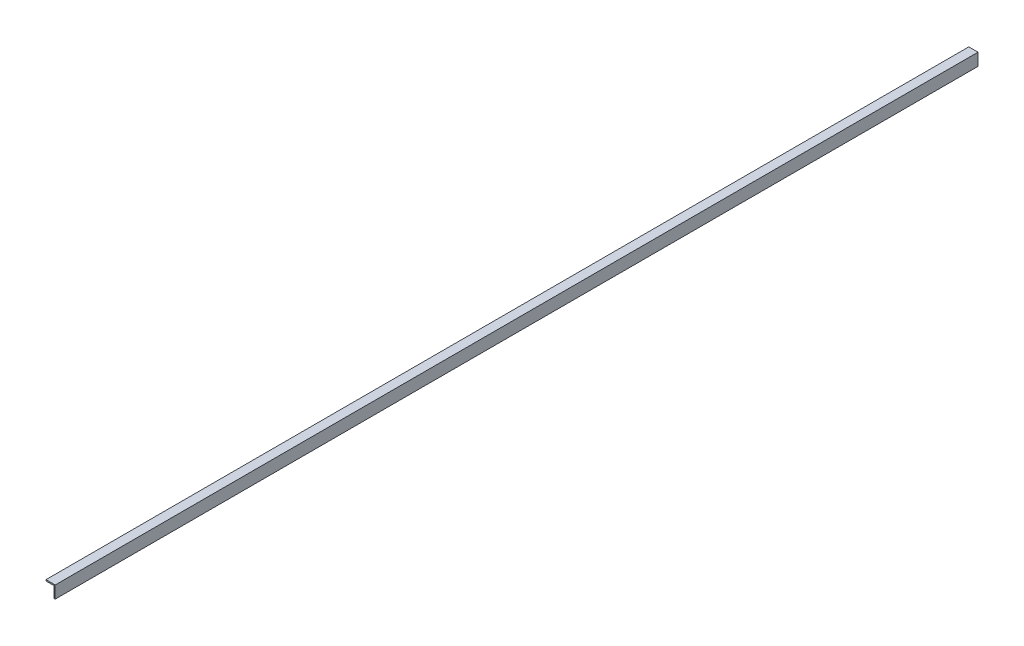
SolidWorks part; units mm, degrees
ref_plane "前视基准面" through (0, 0, 0) normal (0, 0, 1) x (1, 0, 0)
ref_plane "上视基准面" through (0, 0, 0) normal (0, 1, 0) x (1, 0, 0)
ref_plane "右视基准面" through (0, 0, 0) normal (1, 0, 0) x (0, 0, -1)
sketch "草图1" plane through (0, 0, 0) normal (0, 0, 1) x (1, 0, 0)
  line L0 (0, 0) -> (15, 0)
  line L1 (15, 0) -> (15, -20)
  line L2 (0, -2) -> (13, -2)
  line L3 (13, -2) -> (13, -20)
  line L4 (13, -20) -> (15, -20)
  line L5 (0, 0) -> (0, -2)
  dimension "D1" = 15
  dimension "D2" = 20
  dimension "D3" = 2
extrude "凸台-拉伸1" add sketch "草图1" along normal mid plane 1500 contours L0 L1 L4 L3 L2 L5
